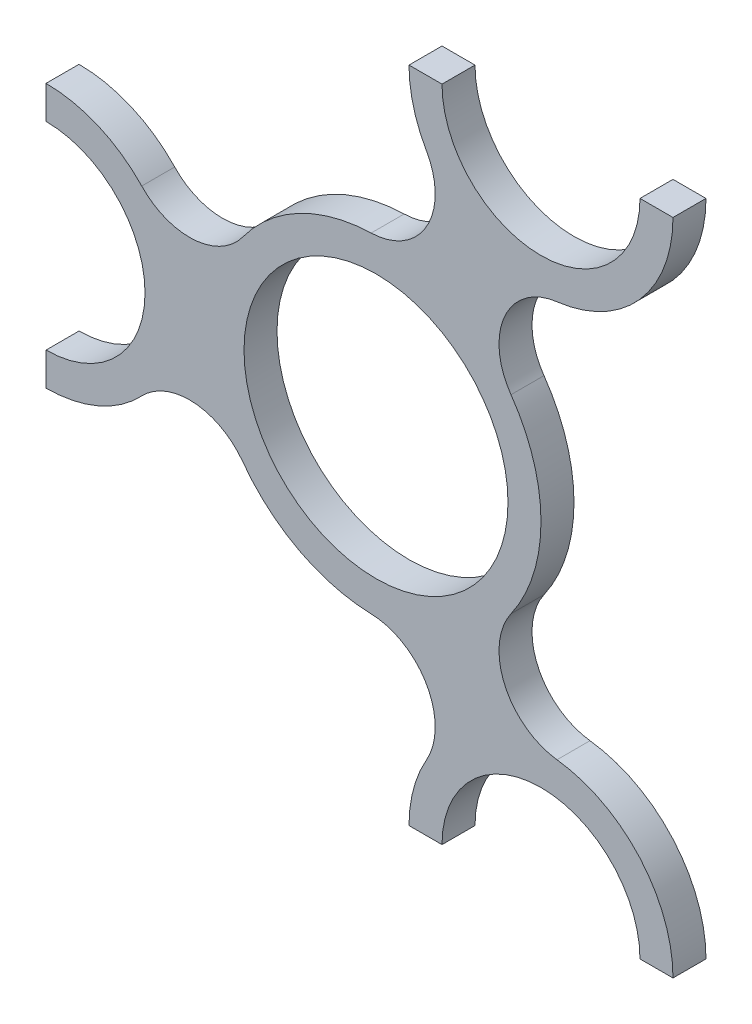
SolidWorks part; units mm, degrees
ref_plane "Front Plane" through (0, 0, 0) normal (0, 0, 1) x (1, 0, 0)
ref_plane "Top Plane" through (0, 0, 0) normal (0, 1, 0) x (1, 0, 0)
ref_plane "Right Plane" through (0, 0, 0) normal (1, 0, 0) x (0, 0, -1)
sketch "Sketch2" plane through (0, 0, 0) normal (0, 0, 1) x (1, 0, 0)
  line L1 (0, -189.8517) -> (0, 0) construction
  line L2 (50, -99.8) -> (50, 99.8) construction
  line L3 (-100, -40) -> (-100, -30)
  line L4 (10, 99.8) -> (20, 99.8)
  line L5 (10, -99.8) -> (20, -99.8)
  line L6 (-100, 30) -> (-100, 40)
  line L7 (80, -99.8) -> (90, -99.8)
  line L8 (80, 99.8) -> (90, 99.8)
  line L9 (0, 50) -> (0, 50.076) construction
  line L10 (0, 0) -> (243.6579, 0) construction
  arc A0 (-1.4708, 49.9784) -> (-40.3571, 29.5178) centre (0, 0) ccw
  circle A1 centre (0, 0) radius 40
  arc A2 (-71, 27.55) -> (-100, 40) centre (-100, 0) ccw
  arc A3 (-100, -30) -> (-100, 30) centre (-100, 0) ccw
  arc A4 (15.2939, -79.9131) -> (10, -99.8) centre (50, -99.8) ccw
  arc A5 (80, -99.8) -> (20, -99.8) centre (50, -99.8) ccw
  arc A6 (54.8505, 60.0952) -> (90, 99.8) centre (50, 99.8) ccw
  arc A7 (20, 99.8) -> (80, 99.8) centre (50, 99.8) ccw
  arc A8 (40.9113, 28.7448) -> (54.8505, 60.0952) centre (57.2758, 40.2428) cw
  arc A9 (40.9113, -28.7448) -> (54.8505, -60.0952) centre (57.2758, -40.2428) ccw
  arc A10 (-71, 27.55) -> (-40.3571, 29.5178) centre (-56.5, 41.3249) ccw
  arc A11 (-40.3571, -29.5178) -> (-71, -27.55) centre (-56.5, -41.3249) ccw
  arc A12 (15.2939, -79.9131) -> (-1.4708, -49.9784) centre (-2.0591, -69.9697) ccw
  arc A13 (-1.4708, 49.9784) -> (15.2939, 79.9131) centre (-2.0591, 69.9697) ccw
  arc A14 (40.9113, -28.7448) -> (40.9113, 28.7448) centre (0, 0) ccw
  arc A15 (-40.3571, -29.5178) -> (-1.4708, -49.9784) centre (0, 0) ccw
  arc A16 (-100, -40) -> (-71, -27.55) centre (-100, 0) ccw
  arc A17 (90, -99.8) -> (54.8505, -60.0952) centre (50, -99.8) ccw
  arc A18 (10, 99.8) -> (15.2939, 79.9131) centre (50, 99.8) ccw
  dimension "D1" = 80
  dimension "D2" = 100
  dimension "D3" = 50
  dimension "D4" = 60
  dimension "D5" = 60
  dimension "D6" = 60
  dimension "D7" = 80
  dimension "D8" = 80
  dimension "D9" = 80
  dimension "D13" = 20
  dimension "D14" = 20
  dimension "D15" = 20
  dimension "D16" = 20
  dimension "D17" = 20
  dimension "D18" = 20
  dimension "D10" = 99.8
  dimension "D11" = 99.8
  dimension "D12" = 100
extrude "Boss-Extrude1" add sketch "Sketch2" along normal blind 10
